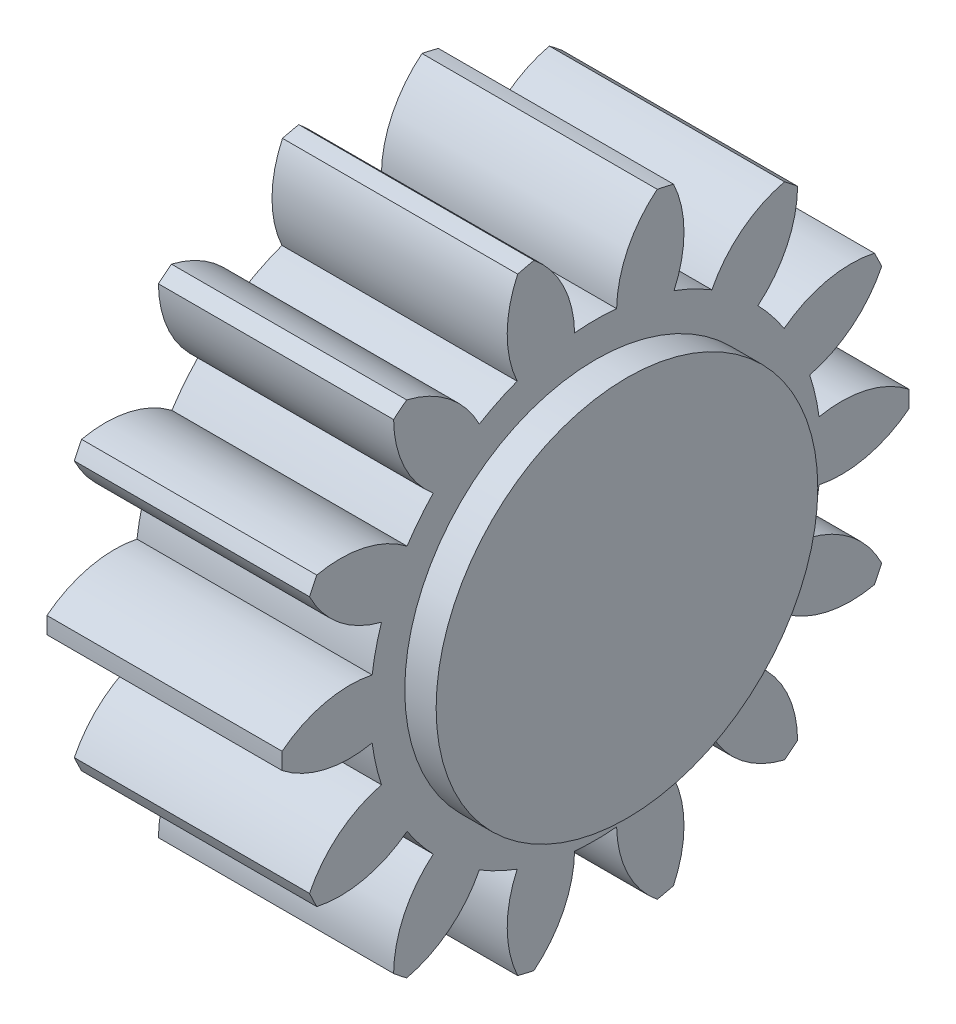
SolidWorks part; units mm, degrees
ref_plane "Plane1" through (0, 0, 0) normal (0, 0, 1) x (1, 0, 0)
ref_plane "Plane2" through (0, 0, 0) normal (0, 1, 0) x (1, 0, 0)
ref_plane "Plane3" through (0, 0, 0) normal (1, 0, 0) x (0, 0, -1)
sketch "HoldingSke" plane through (0, 0, 0) normal (0, 1, 0) x (1, 0, 0)
  line L0 (0, 0) -> (0.3881, -0.0968)
  line L1 (-15, 0) -> (100, 0) construction
  line L2 (0, 0) -> (-2.1039, 2.3779)
  line L3 (0, 0) -> (-11.863, 4.5341)
  line L4 (0, 0) -> (8.3795, 2.0892)
  line L5 (0, 0) -> (-46.8476, -17.4728)
  line L6 (0, 0) -> (-12.4344, -8.3896)
  line L7 (-2.1039, 2.3779) -> (8.6586, 51.2059)
  line L8 (-76.2, 54.61) -> (-75.5, 54.61)
  line L9 (-71.009, 38.7566) -> (-53.1078, 45.2721)
  line L10 (-76.2, 71.12) -> (104.1128, 71.12)
  line L11 (0, 0) -> (-15, 0)
  line L12 (-76.2, 101.6) -> (-76.113, 101.6)
  line L13 (24.9733, 27.94) -> (52.9518, 28.4284)
  line L14 (24.9733, 27.94) -> (24.9743, 27.94)
  line L15 (24.9733, 27.94) -> (100.4006, 29.5858)
  line L16 (-63.627, -2.5) -> (-12.827, -2.5)
  circle A0 centre (0, 0) radius 2
  circle A1 centre (0, 0) radius 14.374
  circle A2 centre (0, 0) radius 37.5
  circle A3 centre (0, 0) radius 2
  dimension "MHD" = 28.748
  dimension "Hub_dia" = 75
  dimension "Bore" = 4
  dimension "MBD" = 4
  dimension "Num_teeth" = 14
  dimension "Pitch" = 0.4
  dimension "Overall_len" = 50
  dimension "Show_teeth" = 14
  dimension "Thickness" = 15
  dimension "OAL" = 50.0001
  dimension "T_dim" = 0.7
  dimension "Ap" = 20
  dimension "H" = 19.05
  dimension "Pitch_radius" = 180.3128
  dimension "Width" = 15
  dimension "Backlash" = 0.087
  dimension "Addendum_fac" = 1
  dimension "Dedendum_fac" = 1.25
  dimension "Clearance_fac" = 0.25
  dimension "Dedendum_add" = 0.001
  dimension "Module" = 2.5
sketch "BasProSke" plane through (0, 0, 0) normal (0, 1, 0) x (1, 0, 0)
  line L0 (-10, 0) -> (60, 0) construction
  line L1 (0, 0) -> (0, 20)
  line L2 (0, 0) -> (15, 0)
  line L3 (15, 0) -> (15, 20)
  line L4 (15, 20) -> (0, 20)
  dimension "Thickness" = 15
  dimension "Diameter" = 40
revolve "Base-Revolve" add sketch "BasProSke" angle 360 about L0
sketch "TooCutSke" plane through (0, 0, 0) normal (1, 0, 0) x (0, 0, -1)
  line L1 (0, 0) -> (0, 107) construction
  line L2 (0, 0) -> (-2.1115, 17.3722) construction
  line L3 (0, 0) -> (-7.7466, 33.9401) construction
  line L4 (-2.1115, 17.3722) -> (-3.8733, 16.97) construction
  arc A0 (1.3395, 14.3115) -> (-1.3395, 14.3115) centre (0, 0) ccw
  arc A1 (3.9542, 19.6311) -> (-3.9542, 19.6311) centre (0, 0) ccw
  circle A2 centre (0, 0) radius 17.5 construction
  circle A3 centre (0, 0) radius 16.4446 construction
  arc A4 (-1.3395, 14.3115) -> (-3.9542, 19.6311) centre (-8.3382, 14.1739) ccw
  arc A5 (3.9542, 19.6311) -> (1.3395, 14.3115) centre (8.3382, 14.1739) ccw
  dimension "Root_dia" = 28.748
  dimension "Overcut_dia" = 40.0508
  dimension "Pitch_dia" = 35
  dimension "Base_dia" = 32.8892
  dimension "Flank_rad" = 7
  dimension "Half_ang" = 12.857
  dimension "Half_CT" = 1.8071
extrude "ToothCut" cut sketch "TooCutSke" along normal through all
fillet "Breaks" [suppressed] radius 0.05
fillet "RootFillets" [suppressed] radius 0.626
pattern_circular "TeethCuts" count 14 every 25.714 about axis through (-10, 0, 0) along (1, 0, 0) of "ToothCut", "RootFillets", "Breaks"
sketch "HubNeaOneSke" plane through (0, 0, 0) normal (-1, 0, 0) x (0, 0, 1)
  circle A0 centre (0, 0) radius 14.374
  dimension "Diameter" = 28.748
extrude "HubNearOne" [suppressed] add sketch "HubNeaOneSke" along normal blind 35.0001
sketch "HubNeaBotSke" plane through (0, 0, 0) normal (-1, 0, 0) x (0, 0, 1)
  circle A0 centre (0, 0) radius 14.374
  dimension "Diameter" = 28.748
extrude "HubNearBoth" [suppressed] add sketch "HubNeaBotSke" along normal blind 17.5
ref_plane "FarPln" through (15, 0, 0) normal (1, 0, 0) x (0, 0, -1)
sketch "HubFarSke" plane through (15, 0, 0) normal (1, 0, 0) x (0, 0, -1)
  circle A0 centre (0, 0) radius 14.374
  dimension "Diameter" = 28.748
extrude "HubFar" [suppressed] add sketch "HubFarSke" along normal blind 17.5
sketch "BorSke" plane through (0, 0, 0) normal (1, 0, 0) x (0, 0, -1)
  circle A0 centre (0, 0) radius 2
  dimension "Diameter" = 4
extrude "Bore" cut sketch "BorSke" along normal mid plane 100.0001
sketch "KeySke" plane through (0, 0, 0) normal (1, 0, 0) x (0, 0, -1)
  line L0 (-0.8, 0) -> (-0.8, 2.7)
  line L1 (-0.8, 2.7) -> (0.8, 2.7)
  line L2 (0.8, 2.7) -> (0.8, 0)
  line L3 (0, 0) -> (0, 34) construction
  line L4 (-0.8, 0) -> (0.8, 0)
  dimension "Offset" = 2.7
  dimension "Width" = 1.6
extrude "Keyway" [suppressed] cut sketch "KeySke" along normal mid plane 100.0001
pattern_circular "Keyway2" [suppressed] count 2 every 90 about axis through (-10, 0, 0) along (1, 0, 0)
sketch "Sketch1" plane through (15, 0, 0) normal (1, 0, 0) x (0, 0, -1)
  circle A0 centre (0, 0) radius 12.1701
extrude "Boss-Extrude1" add sketch "Sketch1" along normal blind 2 contours A0
equation "' \"Module@HoldingSke\" = 6.35"
equation "' \"Num_teeth@HoldingSke\" = 12"
equation "' \"Ap@HoldingSke\" =  20"
equation "' \"Ap@HoldingSke\" = 20"
equation "' \"Width@HoldingSke\" = 0.5 * 25.4"
equation "' \"Hub_dia@HoldingSke\"= 1 * 25.4"
equation "' \"Hub_dia@HoldingSke\" = 1 * 25.4"
equation "' \"Overall_len@HoldingSke\" = 1.0 * 25.4"
equation "' \"Bore@HoldingSke\" = 0.75 * 25.4"
equation "' \"T_dim@HoldingSke\" = 0.1 * 25.4"
equation "' \"Width@KeySke\" = 0.25 * 25.4"
equation "' \"Show_teeth@HoldingSke\" = 13"
equation "' \"Backlash@HoldingSke\" = 0.009 * 25.4"
equation "' \"Addendum_fac@HoldingSke\" = 1.0"
equation "' \"Dedendum_fac@HoldingSke\" = 1.25"
equation "' \"Dedendum_add@HoldingSke\" = 0.00005 * 25.4"
equation "' \"Clearance_fac@HoldingSke\" = 0.25"
equation "\"Pitch@HoldingSke\" = 1 / \"Module@HoldingSke\""
equation "\"Overcut_dia@TooCutSke\" = (\"Num_teeth@HoldingSke\" + 2 * \"Addendum_fac@HoldingSke\") / \"Pitch@HoldingSke\" + 0.002 * 25.4"
equation "\"Pitch_dia@TooCutSke\" = \"Num_teeth@HoldingSke\" / \"Pitch@HoldingSke\""
equation "\"Base_dia@TooCutSke\" = \"Num_teeth@HoldingSke\" / \"Pitch@HoldingSke\" * cos((\"Ap@HoldingSke\"  * 3.14159265 / 180))"
equation "\"Root_dia@TooCutSke\" = (\"Num_teeth@HoldingSke\" + 2) / \"Pitch@HoldingSke\" - 2 * (\"Addendum_fac@HoldingSke\" + \"Dedendum_fac@HoldingSke\") / \"Pitch@HoldingSke\" - \"Dedendum_add@HoldingSke\" * 2"
equation "\"Half_ang@TooCutSke\" = 180 / \"Num_teeth@HoldingSke\""
equation "\"Half_CT@TooCutSke\" = \"Num_teeth@HoldingSke\" / \"Pitch@HoldingSke\" * sin((3.14159265 / 2 / \"Num_teeth@HoldingSke\")) / 2 - 7 * \"Backlash@HoldingSke\" / 4"
equation "\"Flank_rad@TooCutSke\" = \"Num_teeth@HoldingSke\" / \"Pitch@HoldingSke\" / 5"
equation "\"Radius@RootFillets\" = \"Clearance_fac@HoldingSke\" / \"Pitch@HoldingSke\" + \"Dedendum_add@HoldingSke\""
equation "\"Break_rad@Breaks\" = 0.02 / \"Pitch@HoldingSke\""
equation "\"Thickness@HoldingSke\" = \"Width@HoldingSke\""
equation "\"OAL@HoldingSke\" = \"Thickness@HoldingSke\""
equation "\"MHD@HoldingSke\" = (\"Num_teeth@HoldingSke\" + 2) / \"Pitch@HoldingSke\" - 2 * (\"Addendum_fac@HoldingSke\" + \"Dedendum_fac@HoldingSke\")  / \"Pitch@HoldingSke\" - \"Dedendum_add@HoldingSke\" * 2"
equation "\"MBD@HoldingSke\" = (\"Num_teeth@HoldingSke\" + 2) / \"Pitch@HoldingSke\" - 2 * (\"Addendum_fac@HoldingSke\" + \"Dedendum_fac@HoldingSke\")  / \"Pitch@HoldingSke\" - \"Dedendum_add@HoldingSke\" * 2 - 0.002 * 25.4"
equation "\"MHD@HoldingSke\" = ((sgn( \"MHD@HoldingSke\" - \"Hub_dia@HoldingSke\" )-1)*( \"MHD@HoldingSke\" - \"Hub_dia@HoldingSke\" ))/-2+ \"Hub_dia@HoldingSke\""
equation "\"MBD@HoldingSke\" = ((sgn( \"MBD@HoldingSke\" - \"Bore@HoldingSke\" )-1)*( \"MBD@HoldingSke\" - \"Bore@HoldingSke\" ))/-2+ \"Bore@HoldingSke\""
equation "\"OAL@HoldingSke\" = ((sgn( \"OAL@HoldingSke\" - \"Overall_len@HoldingSke\" )+1)*( \"OAL@HoldingSke\" - \"Overall_len@HoldingSke\" ))/2 + \"Overall_len@HoldingSke\" + 0.000002 * 25.4"
equation "\"Num_teeth@TeethCuts\" = int( \"Show_teeth@HoldingSke\" ) + 1"
equation "\"Num_teeth@TeethCuts\" = ((sgn( \"Num_teeth@TeethCuts\" - \"Num_teeth@HoldingSke\" )-1)*( \"Num_teeth@TeethCuts\" - \"Num_teeth@HoldingSke\" ))/-2+ \"Num_teeth@HoldingSke\""
equation "\"Num_teeth@TeethCuts\" = ((sgn( \"Num_teeth@TeethCuts\" - 2.0)+1)*( \"Num_teeth@TeethCuts\" - 2.0))/2 +2.0"
equation "\"Angle@TeethCuts\" = 360.0 / \"Num_teeth@HoldingSke\""
equation "\"Diameter@BasProSke\" = (\"Num_teeth@HoldingSke\" + 2 * \"Addendum_fac@HoldingSke\") / \"Pitch@HoldingSke\""
equation "\"Thickness@BasProSke\"  = \"Thickness@HoldingSke\""
equation "' \"Fillet_rad@BasProSke\" =  \"Thickness@HoldingSke\" * 0.05"
equation "' \"Fillet_rad@BasProSke\" = \"Thickness@HoldingSke\" * 0.05"
equation "\"MHD@HoldingSke\" = ((sgn( \"MHD@HoldingSke\" - \"Root_dia@TooCutSke\" )-1)*( \"MHD@HoldingSke\" - \"Root_dia@TooCutSke\" ))/-2+ \"Root_dia@TooCutSke\""
equation "\"Diameter@HubNeaOneSke\" = \"MHD@HoldingSke\""
equation "\"Length@HubNearOne\" = \"OAL@HoldingSke\" - \"Thickness@BasProSke\""
equation "\"Diameter@HubNeaBotSke\" = \"MHD@HoldingSke\""
equation "\"Length@HubNearBoth\" = ( \"OAL@HoldingSke\" - \"Thickness@BasProSke\" ) / 2.0"
equation "\"Thickness@FarPln\" = \"Thickness@BasProSke\""
equation "\"Diameter@HubFarSke\" = \"MHD@HoldingSke\""
equation "\"Length@HubFar\" = ( \"OAL@HoldingSke\" - \"Thickness@BasProSke\" ) / 2.0"
equation "\"Diameter@BorSke\" = \"MBD@HoldingSke\""
equation "\"D1@Bore\" = \"OAL@HoldingSke\" * 2.0"
equation "\"D1@Keyway\" = \"OAL@HoldingSke\" * 2.0"
equation "\"Offset@KeySke\" = \"T_dim@HoldingSke\" + \"MBD@HoldingSke\" / 2.0"
